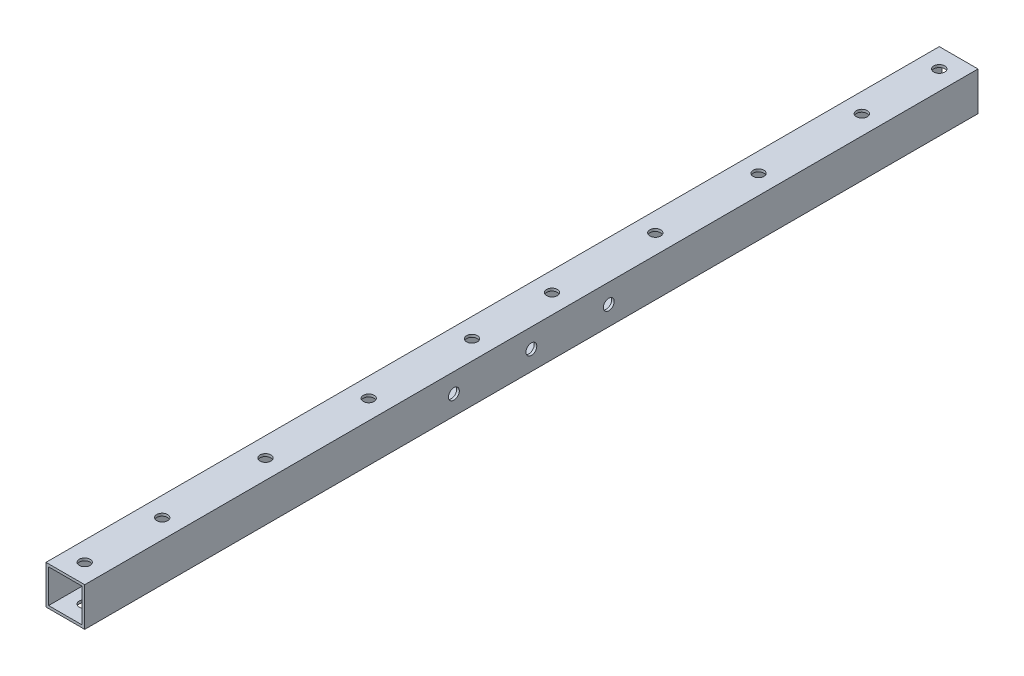
SolidWorks part; units mm, degrees
ref_plane "前视基准面" through (0, 0, 0) normal (0, 0, 1) x (1, 0, 0)
ref_plane "上视基准面" through (0, 0, 0) normal (0, 1, 0) x (1, 0, 0)
ref_plane "右视基准面" through (0, 0, 0) normal (1, 0, 0) x (0, 0, -1)
other "Configuration Table"
sketch "草图1" plane through (0, 0, 0) normal (0, 0, 1) x (1, 0, 0)
  line L1 (-7.5, 7.5) -> (7.5, 7.5)
  line L2 (-7.5, 7.5) -> (-7.5, -7.5)
  line L3 (-7.5, -7.5) -> (7.5, -7.5)
  line L4 (7.5, 7.5) -> (7.5, -7.5)
  line L5 (-7.5, 7.5) -> (7.5, -7.5) construction
  line L6 (-7.5, -7.5) -> (7.5, 7.5) construction
  line L7 (-6.5, 6.5) -> (6.5, 6.5)
  line L8 (-6.5, 6.5) -> (-6.5, -6.5)
  line L9 (-6.5, -6.5) -> (6.5, -6.5)
  line L10 (6.5, 6.5) -> (6.5, -6.5)
  line L11 (-6.5, 6.5) -> (6.5, -6.5) construction
  line L12 (-6.5, -6.5) -> (6.5, 6.5) construction
  point P0 (0, 0)
  point P5 (0, 0)
  dimension "D1" = 15
  dimension "D2" = 15
  dimension "D3" = 1
  dimension "D4" = 1
extrude "凸台-拉伸1" add sketch "草图1" along normal blind 346
sketch "草图3" plane through (0, 7.5, 0) normal (0, 1, 0) x (1, 0, 0)
  line L0 (0, 0) -> (0, -346) construction
  line L1 (7.5, 0) -> (-7.5, 0) construction
  line L2 (7.5, -346) -> (-7.5, -346) construction
  line L3 (-7.5, -173) -> (7.5, -173) construction
  line L4 (-7.5, -346) -> (-7.5, 0) construction
  line L5 (7.5, -346) -> (7.5, 0) construction
  circle A0 centre (0, -338.5) radius 2.1
  circle A1 centre (0, -7.5) radius 2.1
  circle A2 centre (0, -37.5) radius 2.1
  circle A3 centre (0, -308.5) radius 2.1
  circle A4 centre (0, -77.5) radius 2.1
  circle A5 centre (0, -117.5) radius 2.1
  circle A6 centre (0, -228.5) radius 2.1
  circle A7 centre (0, -268.5) radius 2.1
  circle A8 centre (0, -157.5) radius 2.1
  circle A10 centre (0, -188.5) radius 2.1
  dimension "D1" = 4.2
  dimension "D2" = 7.5
  dimension "D3" = 4.2
  dimension "D5" = 40
  dimension "D7" = 40
  dimension "D4" = 30
  dimension "D6" = 40
extrude "切除-拉伸2" cut sketch "草图3" against normal blind 55
sketch "草图4" plane through (7.5, 0, 0) normal (1, 0, 0) x (0, 0, -1)
  line L0 (-346, 0) -> (0, 0) construction
  line L1 (-346, -7.5) -> (-346, 7.5) construction
  line L2 (-173, 7.5) -> (-173, -7.5) construction
  line L3 (-346, 7.5) -> (0, 7.5) construction
  line L4 (-346, -7.5) -> (0, -7.5) construction
  circle A0 centre (-173, 0) radius 2.1
  circle A1 centre (-203, 0) radius 2.1
  circle A2 centre (-143, 0) radius 2.1
  dimension "D1" = 4.2
  dimension "D2" = 60
  dimension "D3" = 4.2
extrude "切除-拉伸3" cut sketch "草图4" against normal blind 55
